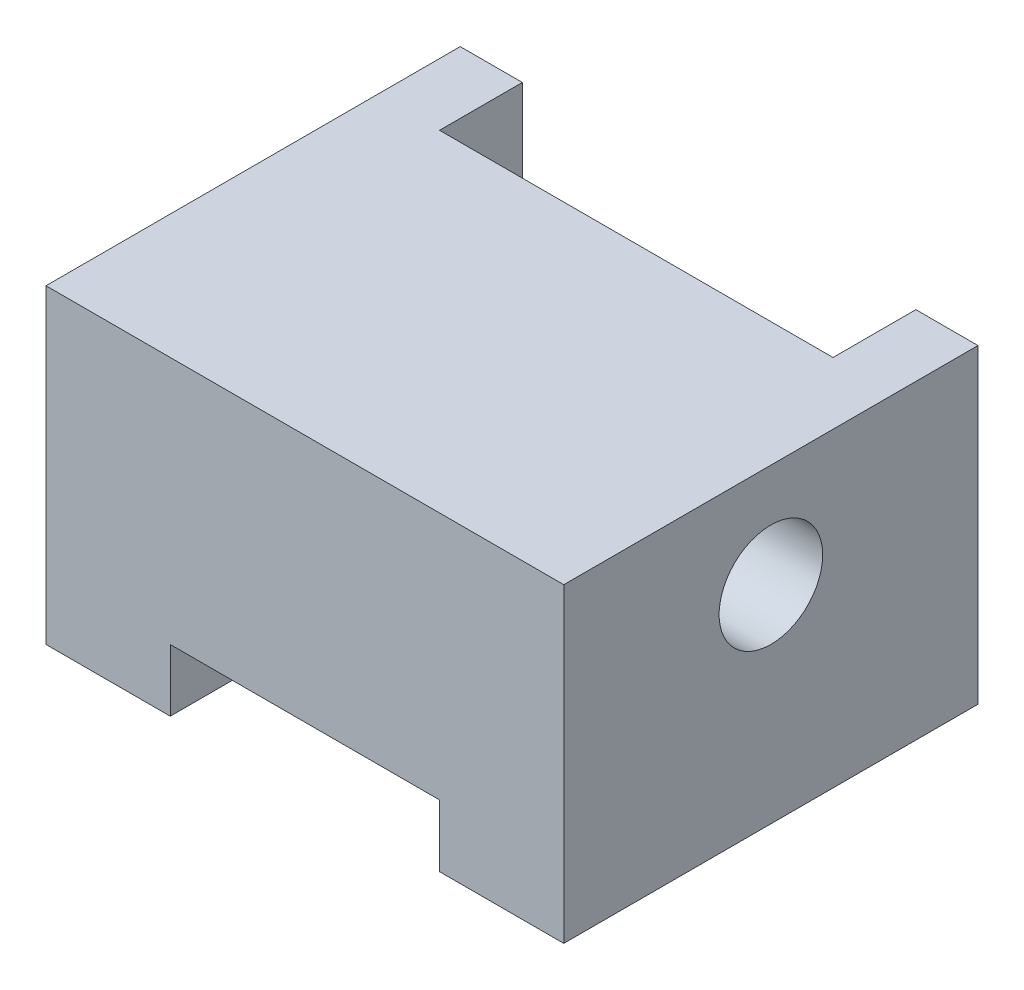
SolidWorks part; units mm, degrees
ref_plane "前基準面" through (0, 0, 0) normal (0, 0, 1) x (1, 0, 0)
ref_plane "上基準面" through (0, 0, 0) normal (0, 1, 0) x (1, 0, 0)
ref_plane "右基準面" through (0, 0, 0) normal (1, 0, 0) x (0, 0, -1)
sketch "草圖1" plane through (0, 0, 0) normal (0, 0, 1) x (1, 0, 0)
  line L1 (-25, -15) -> (25, -15)
  line L2 (-25, -15) -> (-25, 15)
  line L3 (-25, 15) -> (25, 15)
  line L4 (25, -15) -> (25, 15)
  line L5 (-25, -15) -> (25, 15) construction
  line L6 (-25, 15) -> (25, -15) construction
  point P0 (0, 0)
  dimension "D1" = 50
  dimension "D2" = 30
extrude "填料-伸長1" add sketch "草圖1" along normal mid plane 40 contours L3 L4 L1 L2
sketch "草圖2" plane through (0, 0, 0) normal (0, 0, 1) x (1, 0, 0)
  line L0 (-12.941, -15.0195) -> (13.059, -15.0195)
  line L1 (-13, -15) -> (13, -15)
  line L2 (-13, -15) -> (-13, -9)
  line L3 (-13, -9) -> (13, -9)
  line L4 (13, -15) -> (13, -9)
  line L5 (-25, -15) -> (25, -15) construction
  dimension "D1" = 12
  dimension "D2" = 26
  dimension "D3" = 6
extrude "除料-伸長2" cut sketch "草圖2" against normal through all both and the other way through all contours L3 L4 L1 L2
sketch "草圖4" plane through (0, 15, 0) normal (0, 1, 0) x (1, 0, 0)
  line L0 (-25, 20) -> (25, 20) construction
  line L1 (-19, 20) -> (19, 20)
  line L2 (-19, 20) -> (-19, 12)
  line L3 (-19, 12) -> (19, 12)
  line L4 (19, 20) -> (19, 12)
  dimension "D1" = 6
  dimension "D2" = 38
  dimension "D3" = 8
extrude "除料-伸長3" cut sketch "草圖4" against normal through all
sketch "草圖5" plane through (25, 0, 0) normal (1, 0, 0) x (0, 0, -1)
  line L0 (-20, -15) -> (-20, 15) construction
  line L1 (-20, 15) -> (20, 15) construction
  circle A0 centre (0, 5) radius 5
  dimension "D3" = 10
  dimension "D1" = 20
  dimension "D2" = 10
extrude "除料-伸長5" cut sketch "草圖5" against normal blind 27
